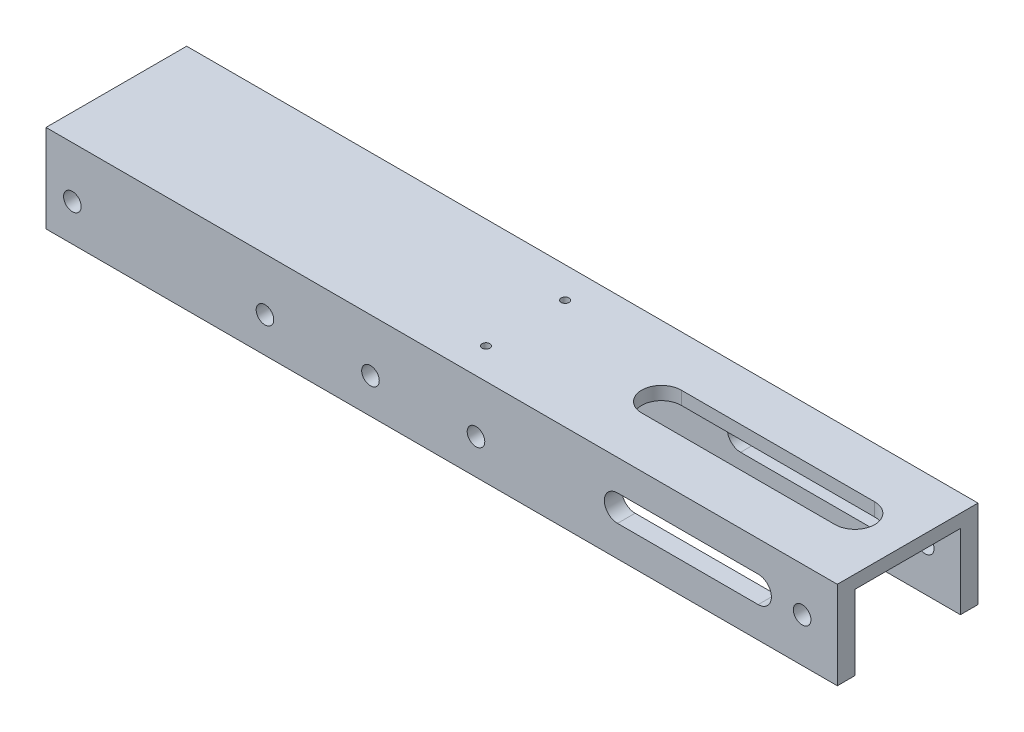
SolidWorks part; units mm, degrees
material "6061-T6 (SS)"
ref_plane "Front Plane" through (0, 0, 0) normal (0, 0, 1) x (1, 0, 0)
ref_plane "Top Plane" through (0, 0, 0) normal (0, 1, 0) x (1, 0, 0)
ref_plane "Right Plane" through (0, 0, 0) normal (1, 0, 0) x (0, 0, -1)
sketch "Sketch1" plane through (0, 0, 0) normal (1, 0, 0) x (0, 0, -1)
  line L0 (-19.05, -31.75) -> (-19.05, -4.7625)
  line L1 (-25.4, 0) -> (25.4, 0)
  line L2 (-25.4, 0) -> (-25.4, -31.75)
  line L3 (-25.4, -31.75) -> (-19.05, -31.75)
  line L4 (25.4, 0) -> (25.4, -31.75)
  line L5 (-19.05, -4.7625) -> (19.05, -4.7625)
  line L6 (19.05, -4.7625) -> (19.05, -31.75)
  line L7 (19.05, -31.75) -> (25.4, -31.75)
  point P6 (0, 0)
  dimension "D1" = 50.8
  dimension "D2" = 6.35
  dimension "D3" = 6.35
  dimension "D4" = 4.7625
  dimension "D5" = 31.75
extrude "Boss-Extrude1" add sketch "Sketch1" along normal blind 285.75
sketch "Sketch2" plane through (0, 0, 25.4) normal (0, 0, 1) x (1, 0, 0)
  line L0 (285.75, 0) -> (285.75, -31.75) construction
  line L1 (0, 0) -> (0, -31.75) construction
  line L2 (79.068, -19.05) -> (155.268, -19.05) construction
  line L3 (285.75, -31.75) -> (0, -31.75) construction
  line L4 (206.375, -15.875) -> (257.175, -15.875) construction
  line L5 (206.375, -11.1125) -> (257.175, -11.1125)
  line L6 (206.375, -20.6375) -> (257.175, -20.6375)
  circle A0 centre (9.525, -18.415) radius 3.175
  arc A1 (206.375, -11.1125) -> (206.375, -20.6375) centre (206.375, -15.875) ccw
  arc A2 (257.175, -20.6375) -> (257.175, -11.1125) centre (257.175, -15.875) ccw
  circle A3 centre (79.068, -19.05) radius 3.175
  circle A4 centre (117.168, -19.05) radius 3.175
  circle A5 centre (155.268, -19.05) radius 3.175
  point P8 (231.775, -15.875)
  dimension "D3" = 6.35
  dimension "D4" = 4.7625
  dimension "D8" = 38.1
  dimension "D9" = 38.1
  dimension "D11" = 79.068
  dimension "D1" = 13.335
  dimension "D2" = 9.525
  dimension "D5" = 28.575
  dimension "D6" = 50.8
  dimension "D7" = 15.875
  dimension "D10" = 12.7
extrude "Cut-Extrude1" cut sketch "Sketch2" against normal through all
sketch "Sketch3" plane through (0, 0, 0) normal (0, 1, 0) x (1, 0, 0)
  line L0 (0, 0) -> (285.75, 0) construction
  line L1 (285.75, 25.4) -> (285.75, -25.4) construction
  line L2 (196.85, 0) -> (266.7, 0) construction
  line L3 (196.85, 7.1437) -> (266.7, 7.1437)
  line L4 (196.85, -7.1437) -> (266.7, -7.1437)
  line L5 (285.75, 25.4) -> (0, 25.4) construction
  line L6 (285.75, -25.4) -> (0, -25.4) construction
  line L7 (0, 25.4) -> (0, -25.4) construction
  arc A0 (196.85, 7.1437) -> (196.85, -7.1437) centre (196.85, 0) ccw
  arc A1 (266.7, -7.1437) -> (266.7, 7.1437) centre (266.7, 0) ccw
  circle A2 centre (147.7645, 14.2875) radius 1.4224
  circle A3 centre (147.7645, -14.2875) radius 1.4224
  point P7 (231.775, 0)
  dimension "D4" = 11.1125
  dimension "D5" = 11.1125
  dimension "D6" = 2.8448
  dimension "D7" = 2.8448
  dimension "D1" = 14.2875
  dimension "D2" = 69.85
  dimension "D3" = 19.05
  dimension "D8" = 147.7645
extrude "Cut-Extrude2" cut sketch "Sketch3" against normal blind 6.35
sketch "Sketch4" plane through (0, 0, 25.4) normal (0, 0, 1) x (1, 0, 0)
  line L0 (285.75, -31.75) -> (0, -31.75) construction
  line L1 (285.75, 0) -> (285.75, -31.75) construction
  circle A0 centre (273.05, -15.875) radius 3.175
  dimension "D1" = 6.35
  dimension "D2" = 15.875
  dimension "D3" = 12.7
extrude "Cut-Extrude3" cut sketch "Sketch4" against normal through all
